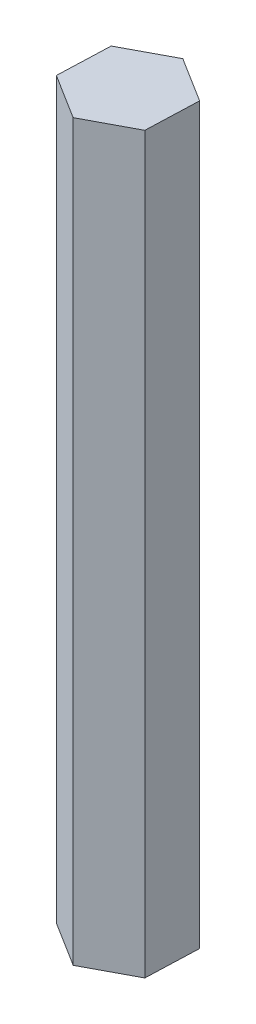
SolidWorks part; units mm, degrees
ref_plane "Front Plane" through (0, 0, 0) normal (0, 0, 1) x (1, 0, 0)
ref_plane "Top Plane" through (0, 0, 0) normal (0, 1, 0) x (1, 0, 0)
ref_plane "Right Plane" through (0, 0, 0) normal (1, 0, 0) x (0, 0, -1)
sketch "Sketch1" plane through (0, 0, 0) normal (0, 1, 0) x (1, 0, 0)
  line L1 (3.2377, 1.72) -> (0.1293, 3.6639)
  line L2 (0.1293, 3.6639) -> (-3.1084, 1.9439)
  line L3 (-3.1084, 1.9439) -> (-3.2377, -1.72)
  line L4 (-3.2377, -1.72) -> (-0.1293, -3.6639)
  line L5 (-0.1293, -3.6639) -> (3.1084, -1.9439)
  line L6 (3.1084, -1.9439) -> (3.2377, 1.72)
  circle A0 centre (0, 0) radius 3.175 construction
  dimension "D1" = 6.35
extrude "Boss-Extrude1" add sketch "Sketch1" along normal blind 50.8
